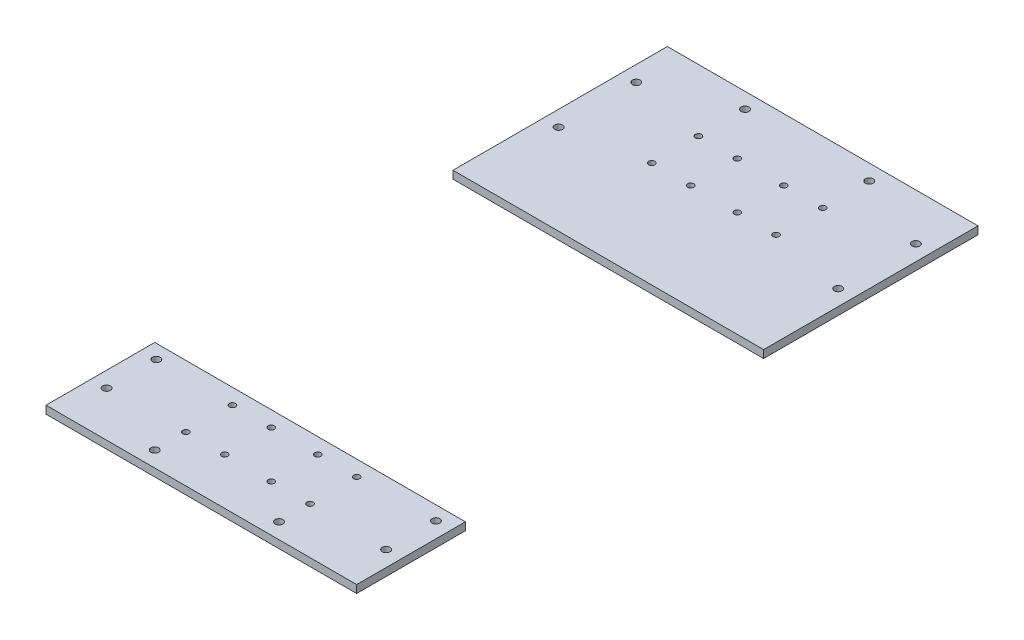
SolidWorks part; units mm, degrees
ref_plane "前视基准面" through (0, 0, 0) normal (0, 0, 1) x (1, 0, 0)
ref_plane "上视基准面" through (0, 0, 0) normal (0, 1, 0) x (1, 0, 0)
ref_plane "右视基准面" through (0, 0, 0) normal (1, 0, 0) x (0, 0, -1)
sketch "草图1" plane through (0, 0, 0) normal (0, 1, 0) x (1, 0, 0)
  line L1 (0, 0) -> (200, 0)
  line L2 (0, 0) -> (0, 70)
  line L3 (0, 70) -> (200, 70)
  line L4 (200, 0) -> (200, 70)
  line L5 (0, 262) -> (200, 262)
  line L6 (0, 262) -> (0, 400)
  line L7 (0, 400) -> (200, 400)
  line L8 (200, 262) -> (200, 400)
  dimension "D1" = 200
  dimension "D2" = 400
  dimension "D3" = 138
  dimension "D4" = 70
extrude "凸台-拉伸1" add sketch "草图1" along normal blind 5
hole_wizard "Ø4.0 (4) 直径孔1" positions "草图3" profile "草图2" hole size "Ø4.0" standard "GB" end condition through all
sketch "草图3" plane through (0, 5, 0) normal (0, 1, 0) x (1, 0, 0)
  line L0 (0, 0) -> (200, 0) construction
  line L1 (0, 70) -> (0, 0) construction
  line L2 (200, 0) -> (200, 70) construction
  point P0 (60, 360)
  point P2 (85, 360)
  point P4 (60, 330)
  point P6 (85, 330)
  point P8 (115, 360)
  point P10 (140, 360)
  point P12 (115, 330)
  point P14 (140, 330)
  point P16 (60, 60)
  point P18 (85, 60)
  point P20 (60, 30)
  point P22 (85, 30)
  point P24 (115, 60)
  point P26 (140, 60)
  point P28 (115, 30)
  point P30 (140, 30)
  dimension "D1" = 30
  dimension "D2" = 30
  dimension "D3" = 25
  dimension "D4" = 25
  dimension "D5" = 30
  dimension "D6" = 270
  dimension "D7" = 60
  dimension "D8" = 60
sketch "草图2" plane through (60, 5, -360) normal (1, 0, 0) x (0, 0, 1)
  line L0 (0, 0) -> (0, 5)
  line L1 (0, 5) -> (2, 5)
  line L2 (2, 5) -> (2, 0)
  line L5 (2, 0) -> (0, 0)
  line L11 (0, -6.35) -> (0, 107.95) construction
  dimension "通孔孔直径" = 4
  dimension "通孔孔深度" = 5
hole_wizard "Ø5.0 (5) 直径孔1" positions "草图5" profile "草图4" hole size "Ø5.0" standard "GB" end condition through all
sketch "草图5" plane through (0, 5, 0) normal (0, 1, 0) x (1, 0, 0)
  line L0 (0, 400) -> (0, 262) construction
  line L1 (0, 0) -> (200, 0) construction
  line L2 (200, 400) -> (0, 400) construction
  line L3 (60, 360) -> (60, 330) construction
  line L5 (60, 60) -> (60, 30) construction
  line L7 (10, 61) -> (10, 29) construction
  line L9 (10, 45) -> (60, 45) construction
  line L12 (10, 370) -> (10, 320) construction
  line L14 (10, 345) -> (60, 345) construction
  line L15 (200, 262) -> (200, 400) construction
  point P0 (10, 370)
  point P2 (10, 320)
  point P4 (190, 370)
  point P6 (190, 320)
  point P8 (190, 61)
  point P10 (190, 29)
  point P12 (10, 61)
  point P14 (10, 29)
  point P16 (60, 390)
  point P18 (140, 390)
  point P20 (60, 10)
  point P22 (140, 10)
  dimension "D1" = 32
  dimension "D2" = 50
  dimension "D3" = 80
  dimension "D4" = 60
  dimension "D5" = 10
  dimension "D6" = 10
  dimension "D7" = 10
  dimension "D8" = 10
sketch "草图4" plane through (10, 5, -370) normal (1, 0, 0) x (0, 0, 1)
  line L0 (0, 0) -> (0, 5)
  line L1 (0, 5) -> (2.5, 5)
  line L2 (2.5, 5) -> (2.5, 0)
  line L5 (2.5, 0) -> (0, 0)
  line L11 (0, -6.35) -> (0, 107.95) construction
  dimension "通孔孔直径" = 5
  dimension "通孔孔深度" = 5
